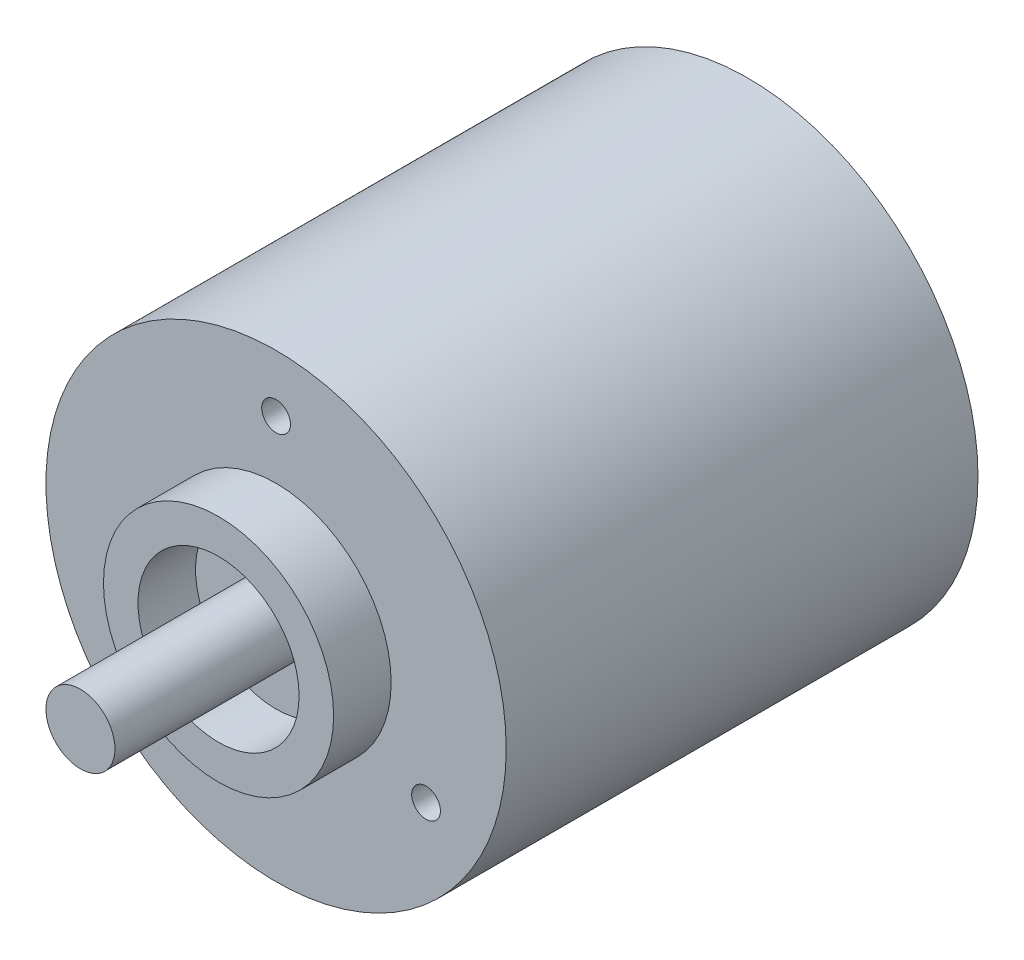
SolidWorks part; units mm, degrees
ref_plane "Plan de face" through (0, 0, 0) normal (0, 0, 1) x (1, 0, 0)
ref_plane "Plan de dessus" through (0, 0, 0) normal (0, 1, 0) x (1, 0, 0)
ref_plane "Plan de droite" through (0, 0, 0) normal (1, 0, 0) x (0, 0, -1)
sketch "Esquisse1" plane through (0, 0, 0) normal (0, 0, 1) x (1, 0, 0)
  circle A0 centre (0, 0) radius 20
  dimension "D1" = 40
extrude "Boss.-Extru.1" add sketch "Esquisse1" against normal blind 41
sketch "Esquisse2" plane through (0, 0, 0) normal (0, 0, 1) x (1, 0, 0)
  circle A0 centre (0, 0) radius 10
  circle A1 centre (0, 0) radius 7
  dimension "D1" = 20
  dimension "D2" = 3
extrude "Boss.-Extru.2" add sketch "Esquisse2" along normal blind 5
sketch "Esquisse3" plane through (0, 0, 0) normal (0, 0, 1) x (1, 0, 0)
  circle A0 centre (0, 0) radius 3
  dimension "D1" = 6
extrude "Boss.-Extru.3" add sketch "Esquisse3" along normal blind 17
sketch "Esquisse4" plane through (0, 0, 0) normal (0, 0, 1) x (1, 0, 0)
  line L0 (0, -21.5832) -> (0, 21.5832) construction
  circle A0 centre (0, 15.05) radius 1.25
  circle A2 centre (13.0337, -7.525) radius 1.25
  circle A3 centre (-13.0337, -7.525) radius 1.25
  point P12 (0, 0)
  dimension "D1" = 2.5
  dimension "D2" = 15.05
  dimension "D4" = 15.05
  dimension "D3" = 3
extrude "Enlèv. mat.-Extru.1" cut sketch "Esquisse4" against normal blind 7.9
